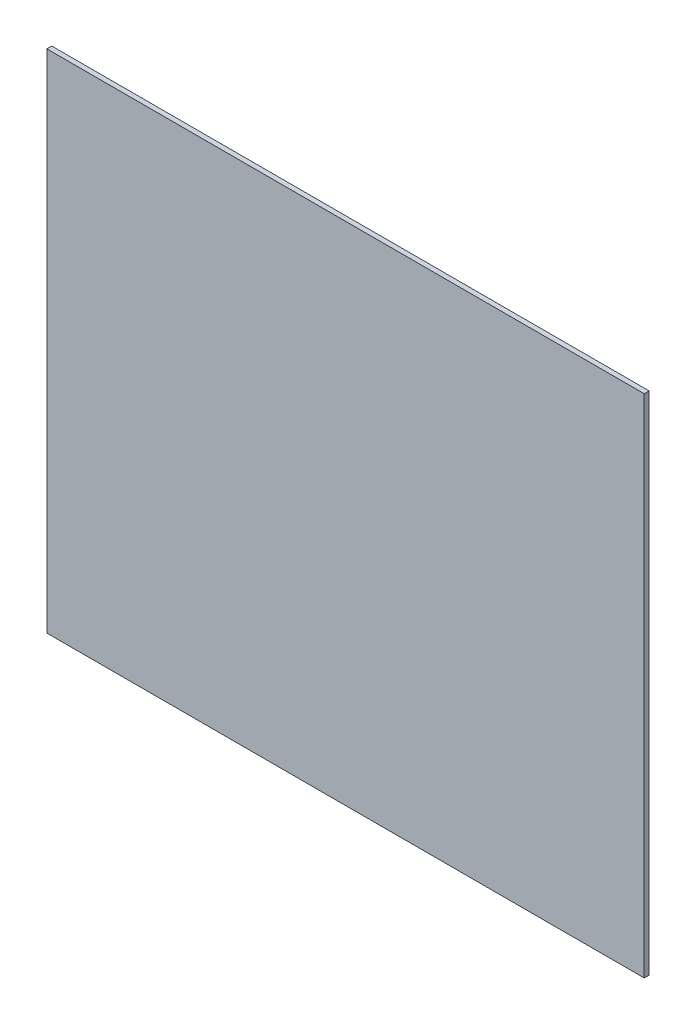
SolidWorks part; units mm, degrees
ref_plane "前视基准面" through (0, 0, 0) normal (0, 0, 1) x (1, 0, 0)
ref_plane "上视基准面" through (0, 0, 0) normal (0, 1, 0) x (1, 0, 0)
ref_plane "右视基准面" through (0, 0, 0) normal (1, 0, 0) x (0, 0, -1)
other "Configuration Table"
sketch "草图1" plane through (0, 0, 0) normal (0, 0, 1) x (1, 0, 0)
  line L1 (0, 0) -> (366, 0)
  line L2 (0, 0) -> (0, 310)
  line L3 (0, 310) -> (366, 310)
  line L4 (366, 0) -> (366, 310)
  dimension "D1" = 310
  dimension "D2" = 366
extrude "凸台-拉伸1" add sketch "草图1" along normal blind 3
